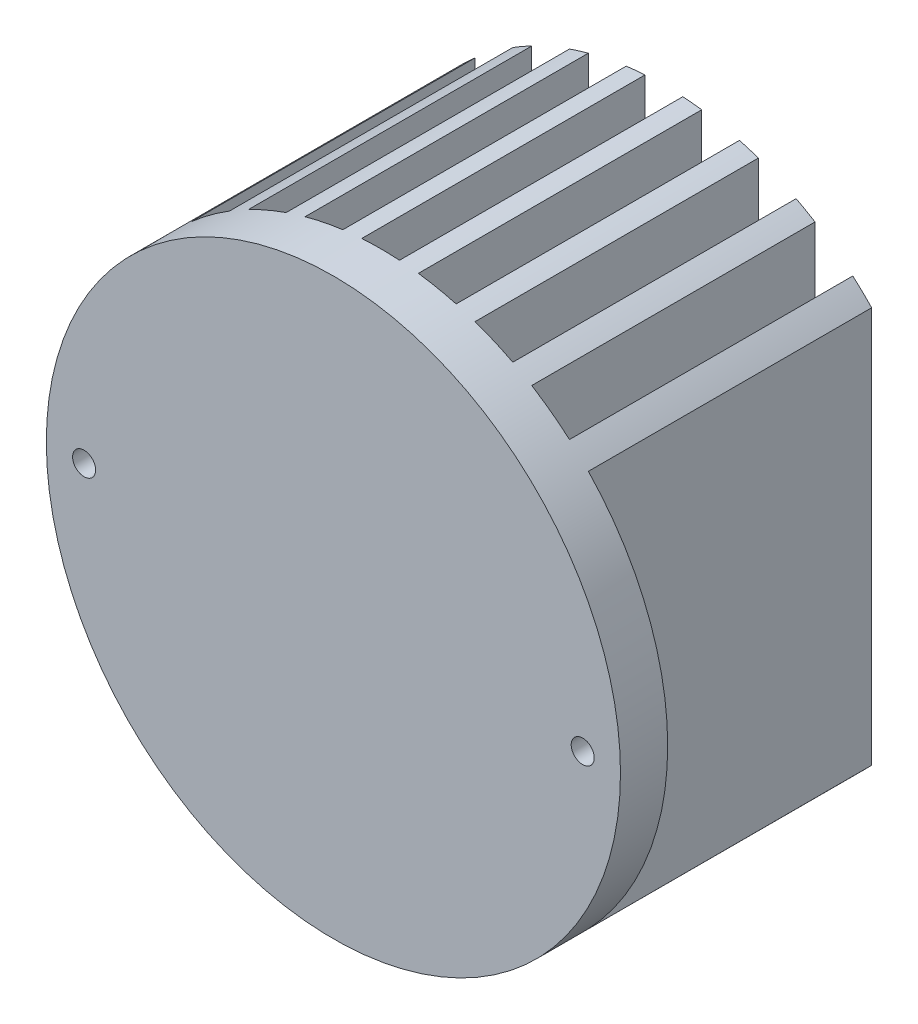
SolidWorks part; units mm, degrees
ref_plane "Plan de face" through (0, 0, 0) normal (0, 0, 1) x (1, 0, 0)
ref_plane "Plan de dessus" through (0, 0, 0) normal (0, 1, 0) x (1, 0, 0)
ref_plane "Plan de droite" through (0, 0, 0) normal (1, 0, 0) x (0, 0, -1)
sketch "Sketch1" plane through (0, 0, 0) normal (0, 0, 1) x (1, 0, 0)
  circle A0 centre (0, 0) radius 30.4
extrude "Boss-Extrude1" add sketch "Sketch1" along normal blind 35
sketch "Sketch4" plane through (0, 0, 0) normal (0, 0, -1) x (-1, 0, 0)
  line L1 (2, -30.4) -> (-2, -30.4)
  line L2 (2, -30.4) -> (2, 30.4)
  line L3 (2, 30.4) -> (-2, 30.4)
  line L4 (-2, -30.4) -> (-2, 30.4)
  point P4 (0, 0)
  point P5 (0, 0)
  point P6 (0, 0)
  point P7 (0, 0)
  point P8 (0, 0)
  point P9 (0, 0)
  point P10 (0, 0)
  point P11 (0, 0)
  point P12 (0, 0)
  point P13 (0, 0)
  point P14 (0, 0)
  point P15 (0, 0)
  point P16 (0, 0)
extrude "Cut-Extrude1" cut sketch "Sketch4" against normal blind 30
pattern_linear "LPattern1" count 5 spacing 6 along (1, 0, 0) of "Cut-Extrude1"
mirror "Mirror1" about plane through (0, 0, 0) normal (1, 0, 0) of "LPattern1"
sketch "Sketch9" plane through (0, 0, 0) normal (0, 0, -1) x (-1, 0, 0)
  line L1 (-26, -15.7531) -> (-30.4, -15.7531)
  line L2 (-26, -15.7531) -> (-26, 15.7531)
  line L3 (-26, 15.7531) -> (-30.4, 15.7531)
  line L4 (-30.4, -15.7531) -> (-30.4, 15.7531)
  line L5 (26, 15.7531) -> (30.4, 15.7531)
  line L6 (26, 15.7531) -> (26, -15.7531)
  line L7 (26, -15.7531) -> (30.4, -15.7531)
  line L8 (30.4, 15.7531) -> (30.4, -15.7531)
extrude "Cut-Extrude2" cut sketch "Sketch9" against normal blind 30
sketch "Sketch12" plane through (0, 0, 30) normal (0, 0, -1) x (-1, 0, 0)
  line L0 (-30.4, 0) -> (-26.4, 0)
  arc A0 (-22, 20.98) -> (-22, -20.98) centre (0, 0) ccw construction
hole_wizard "CBORE for #2 Binding Head Machine Screw2" positions "Sketch13" profile "Sketch14" counterbore size "#2" standard "ANSI Inch"
sketch "Sketch13" plane through (0, 0, 30) normal (0, 0, -1) x (-1, 0, 0)
  point P0 (-26.4, 0)
sketch "Sketch14" plane through (26.4, 0, 30) normal (1, 0, 0) x (0, 1, 0)
  line L0 (0, 0) -> (0, 5.7326)
  line L1 (0, 5.7326) -> (1.2192, 5)
  line L2 (1.2192, 5) -> (1.2192, 1.27)
  line L3 (1.2192, 1.27) -> (2.7788, 1.27)
  line L4 (2.7788, 1.27) -> (2.7788, 0)
  line L5 (2.7788, 0) -> (0, 0)
  line L10 (0, 5.7326) -> (-1.2192, 5) construction
  line L11 (0, -6.35) -> (0, 107.95) construction
  dimension "Hole Dia." = 2.4384
  dimension "Hole Depth" = 5
  dimension "C'Bore Dia." = 5.5575
  dimension "C'Bore Depth" = 1.27
  dimension "Drill Angle" = 118
mirror "Mirror2" about plane through (0, 0, 0) normal (1, 0, 0) of "CBORE for #2 Binding Head Machine Screw2"
